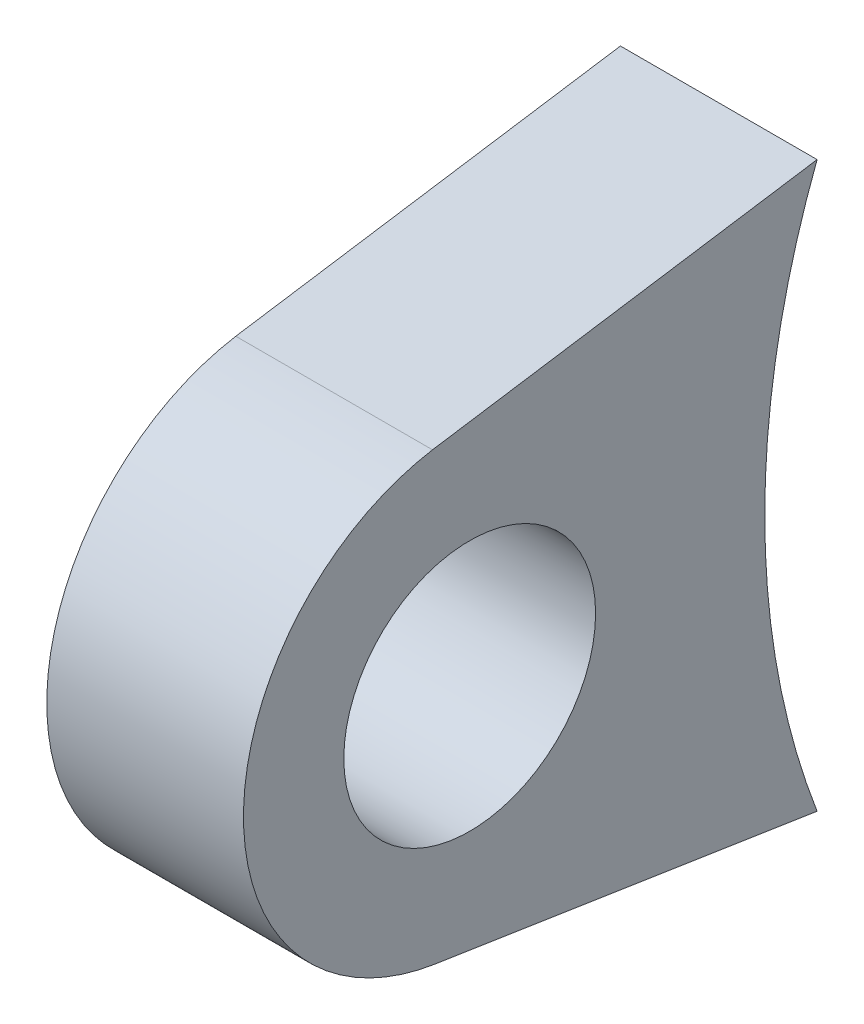
SolidWorks part; units mm, degrees
material "6061 Alloy"
ref_plane "Płaszczyzna przednia" through (0, 0, 0) normal (0, 0, 1) x (1, 0, 0)
ref_plane "Płaszczyzna górna" through (0, 0, 0) normal (0, 1, 0) x (1, 0, 0)
ref_plane "Płaszczyzna prawa" through (0, 0, 0) normal (1, 0, 0) x (0, 0, -1)
sketch "Szkic19" plane through (91.7854, 0, 0) normal (1, 0, 0) x (0, 0, -1)
  line L0 (-27.5, 0) -> (0, 0)
  line L1 (-28.446, 5.6717) -> (-18.6696, 7.1726)
  line L2 (-18.6696, 7.1726) -> (-18.6696, -7.1726)
  line L3 (-18.6696, -7.1726) -> (-28.3723, -5.6835)
  circle A0 centre (0, 0) radius 20
  circle A1 centre (-27.5, 0) radius 3.2
  circle A2 centre (-27.5, 0) radius 5.75
  circle A3 centre (0, 0) radius 20 construction
  dimension "D2" = 11.5
extrude "Dodanie-wyciągnięcie4" add sketch "Szkic19" against normal blind 5
